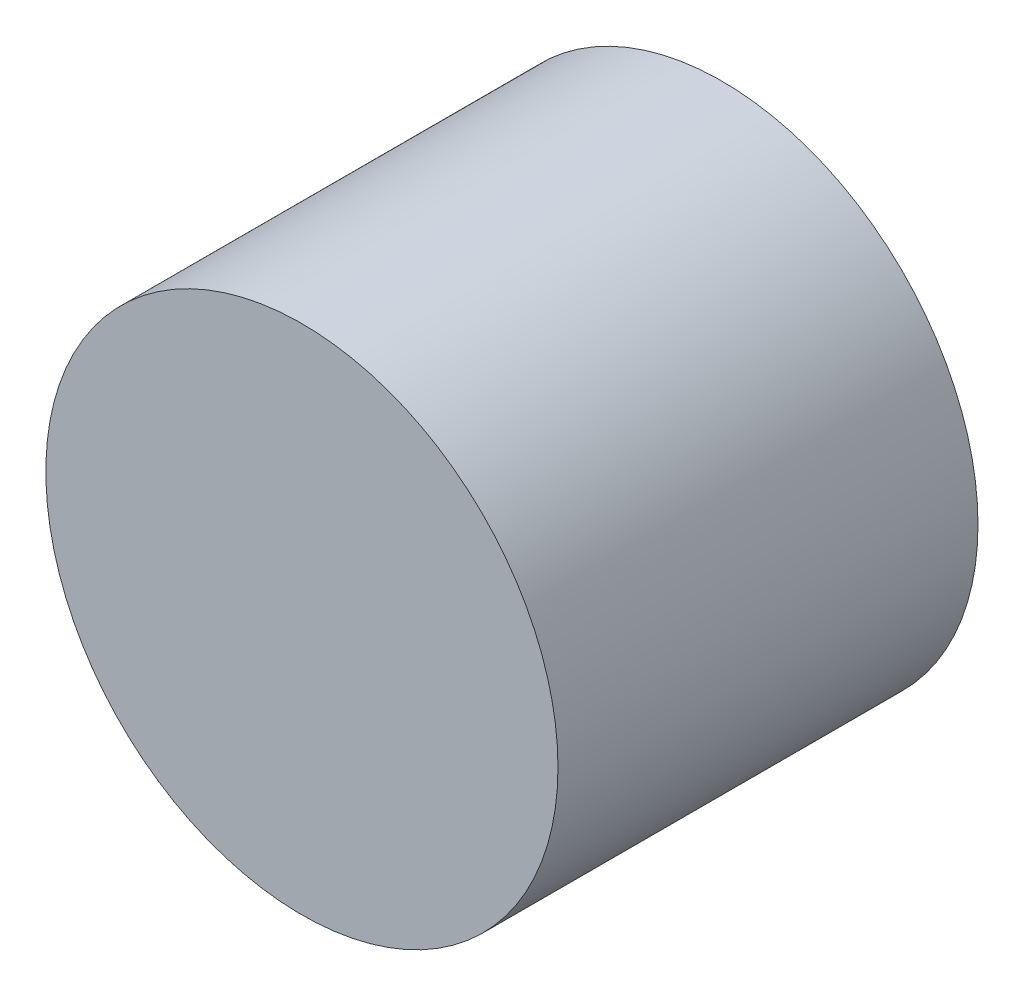
SolidWorks part; units mm, degrees
ref_plane "Front Plane" through (0, 0, 0) normal (0, 0, 1) x (1, 0, 0)
ref_plane "Top Plane" through (0, 0, 0) normal (0, 1, 0) x (1, 0, 0)
ref_plane "Right Plane" through (0, 0, 0) normal (1, 0, 0) x (0, 0, -1)
sketch "Sketch1" plane through (0, 0, 0) normal (0, 0, 1) x (1, 0, 0)
  circle A0 centre (0, 0) radius 9.755
extrude "Envelope" add sketch "Sketch1" along normal blind 16
